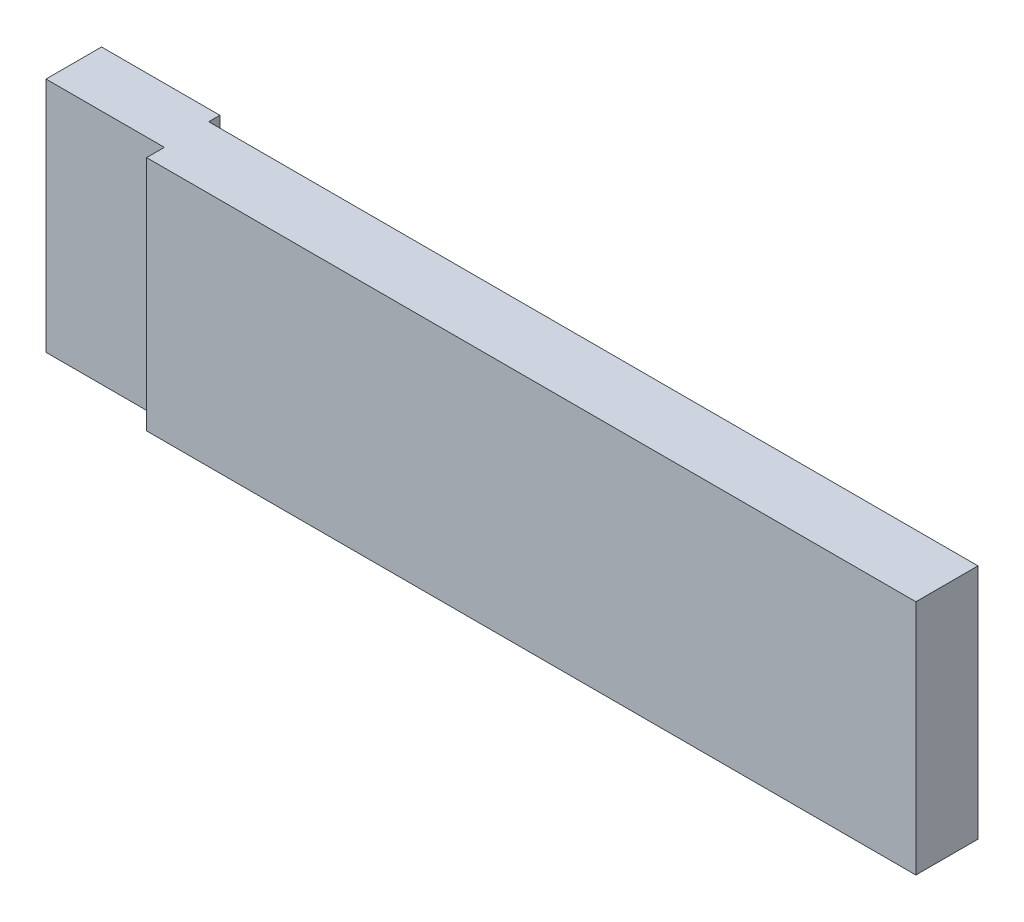
SolidWorks part; units mm, degrees
ref_plane "Piano frontale" through (0, 0, 0) normal (0, 0, 1) x (1, 0, 0)
ref_plane "Piano superiore" through (0, 0, 0) normal (0, 1, 0) x (1, 0, 0)
ref_plane "Piano destro" through (0, 0, 0) normal (1, 0, 0) x (0, 0, -1)
sketch "Schizzo1" plane through (0, 0, 0) normal (0, 0, 1) x (1, 0, 0)
  line L5 (-7.5, 2) -> (7.5, 2)
  line L6 (-7.5, 2) -> (-7.5, -2)
  line L7 (-7.5, -2) -> (7.5, -2)
  line L8 (7.5, 2) -> (7.5, -2)
  line L9 (-7.5, 2) -> (7.5, -2) construction
  line L10 (-7.5, -2) -> (7.5, 2) construction
  point P0 (0, 0)
  dimension "D1" = 15
  dimension "D2" = 4
extrude "Estrusione-Estrusione1" add sketch "Schizzo1" against normal blind 1.5
sketch "Schizzo2" plane through (0, 0, 0) normal (0, 0, 1) x (1, 0, 0)
  line L0 (7.5, 2) -> (7.5, -2)
  line L1 (7.5, 2) -> (-5.5, 2)
  line L2 (7.5, -2) -> (-5.5, -2)
  line L3 (-5.5, 2) -> (-5.5, -2)
  dimension "D1" = 13
  dimension "D2" = 4
extrude "Estrusione-Estrusione2" add sketch "Schizzo2" along normal blind 0.3
sketch "Schizzo3" plane through (0, 2, 0) normal (0, 1, 0) x (1, 0, 0)
  line L0 (-7.5, 1.5) -> (7.5, 1.5)
  line L2 (-7.6609, 0.75) -> (-7.6609, 1.5011)
  line L4 (7.5, 1.5) -> (7.5, -0.3) construction
  line L5 (7.5, 0.75) -> (-5.5, 0.75)
  line L7 (-7.5, 1.5) -> (-7.6609, 1.5011)
  line L8 (7.5, 1.5) -> (7.5, 0.75)
  line L9 (-5.5, 0.9387) -> (-7.5, 0.9387)
  line L10 (-7.5, 1.5) -> (-7.5, 0) construction
  line L11 (-7.5, 0.9387) -> (-7.5, 0.75)
  line L13 (-5.5, 0.75) -> (-5.5, 0.9387)
  line L14 (-7.5, 0.75) -> (-7.6609, 0.75)
extrude "Taglio-Estrusione1" cut sketch "Schizzo3" against normal blind 4
